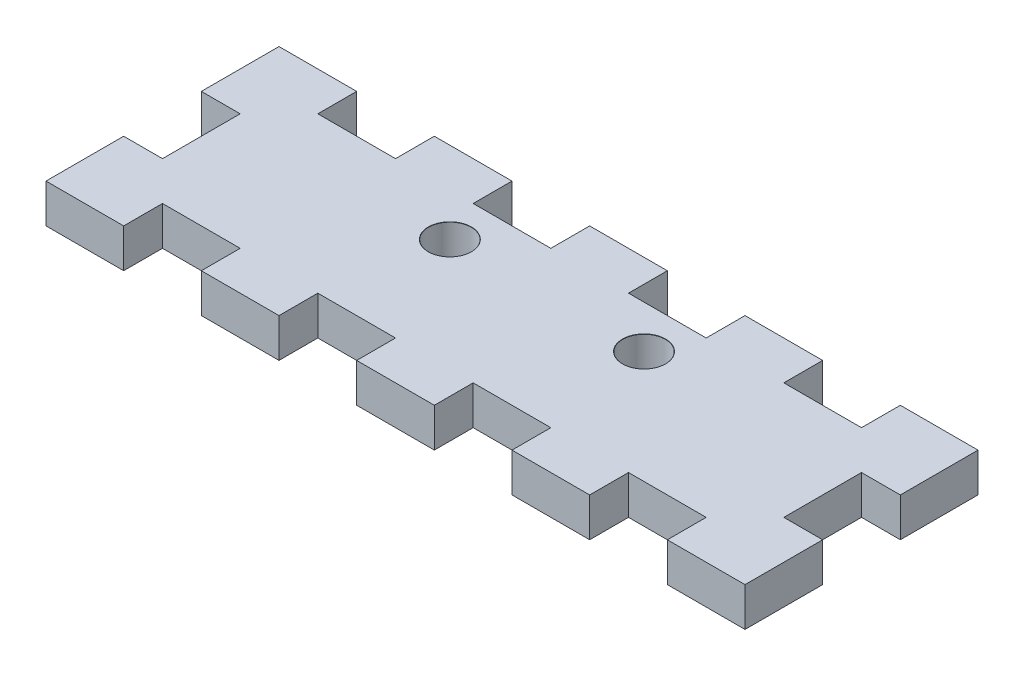
SolidWorks part; units mm, degrees
ref_plane "Front Plane" through (0, 0, 0) normal (0, 0, 1) x (1, 0, 0)
ref_plane "Top Plane" through (0, 0, 0) normal (0, 1, 0) x (1, 0, 0)
ref_plane "Right Plane" through (0, 0, 0) normal (1, 0, 0) x (0, 0, -1)
sketch "Sketch1" plane through (0, 0, 0) normal (0, 1, 0) x (1, 0, 0)
  line L0 (45, 15) -> (40, 15)
  line L1 (40, 15) -> (35, 15)
  line L2 (35, 15) -> (35, 10)
  line L3 (35, 10) -> (25, 10)
  line L4 (25, 10) -> (25, 15)
  line L5 (25, 15) -> (15, 15)
  line L6 (15, 15) -> (15, 10)
  line L7 (15, 10) -> (5, 10)
  line L8 (5, 10) -> (5, 15)
  line L9 (5, 15) -> (-5, 15)
  line L10 (-5, 15) -> (-5, 10)
  line L11 (-5, 10) -> (-15, 10)
  line L12 (-15, 10) -> (-15, 15)
  line L13 (-15, 15) -> (-25, 15)
  line L14 (-25, 15) -> (-25, 10)
  line L15 (-25, 10) -> (-35, 10)
  line L16 (-35, 10) -> (-35, 15)
  line L17 (-35, 15) -> (-40, 15)
  line L18 (-40, 15) -> (-45, 15)
  line L19 (-45, 15) -> (-45, 10)
  line L20 (-45, 10) -> (-45, 5)
  line L21 (-45, 5) -> (-40, 5)
  line L22 (-40, 5) -> (-40, -5)
  line L23 (-40, -5) -> (-45, -5)
  line L24 (-45, -5) -> (-45, -10)
  line L25 (-45, -10) -> (-45, -15)
  line L26 (-45, -15) -> (-40, -15)
  line L27 (-40, -15) -> (-35, -15)
  line L28 (-35, -15) -> (-35, -10)
  line L29 (-35, -10) -> (-25, -10)
  line L30 (-25, -10) -> (-25, -15)
  line L31 (-25, -15) -> (-15, -15)
  line L32 (-15, -15) -> (-15, -10)
  line L33 (-15, -10) -> (-5, -10)
  line L34 (-5, -10) -> (-5, -15)
  line L35 (-5, -15) -> (5, -15)
  line L36 (5, -15) -> (5, -10)
  line L37 (5, -10) -> (15, -10)
  line L38 (15, -10) -> (15, -15)
  line L39 (15, -15) -> (25, -15)
  line L40 (25, -15) -> (25, -10)
  line L41 (25, -10) -> (35, -10)
  line L42 (35, -10) -> (35, -15)
  line L43 (35, -15) -> (40, -15)
  line L44 (40, -15) -> (45, -15)
  line L45 (45, -15) -> (45, -10)
  line L46 (45, -10) -> (45, -5)
  line L47 (45, -5) -> (40, -5)
  line L48 (40, -5) -> (40, 5)
  line L49 (40, 5) -> (45, 5)
  line L50 (45, 5) -> (45, 10)
  line L51 (45, 10) -> (45, 15)
  line L52 (-45, 15) -> (45, -15) construction
  point P52 (0, 0)
extrude "Boss-Extrude1" add sketch "Sketch1" along normal mid plane 5
sketch "Sketch2" plane through (0, 2.5, 0) normal (0, 1, 0) x (1, 0, 0)
  text T0 "Left/Right\r\n"
extrude "Cut-Extrude1" [suppressed] cut sketch "Sketch2" against normal blind 3
sketch "Sketch3" plane through (0, 2.5, 0) normal (0, 1, 0) x (1, 0, 0)
  line L0 (0, 27.7931) -> (0, -35.4399) construction
  line L1 (-12.5, 4.5) -> (12.5, 4.5) construction
  line L2 (5, 15) -> (-5, 15) construction
  point P3 (-12.5, 4.5)
  point P4 (12.5, 4.5)
  point P5 (0, 4.5)
  dimension "D1" = 25
  dimension "D2" = 10.5
hole_wizard "M5 Clearance Hole1" positions "Sketch3" profile "Sketch4" hole size "M5" standard "ISO" end condition through all
sketch "Sketch4" plane through (12.5, 2.5, -4.5) normal (1, 0, 0) x (0, 0, 1)
  line L0 (0, 0) -> (0, 5)
  line L1 (0, 5) -> (2.75, 5)
  line L2 (2.75, 5) -> (2.75, 0.025)
  line L3 (2.75, 0.025) -> (2.775, 0)
  line L5 (2.775, 0) -> (0, 0)
  line L6 (-2.75, 0.025) -> (-2.775, 0) construction
  line L11 (0, -6.35) -> (0, 107.95) construction
  dimension "Thru Hole Dia." = 5.5
  dimension "Thru Hole Depth" = 5
  dimension "Near C'Sink Dia." = 5.55
  dimension "Near C'Sink Angle" = 90
